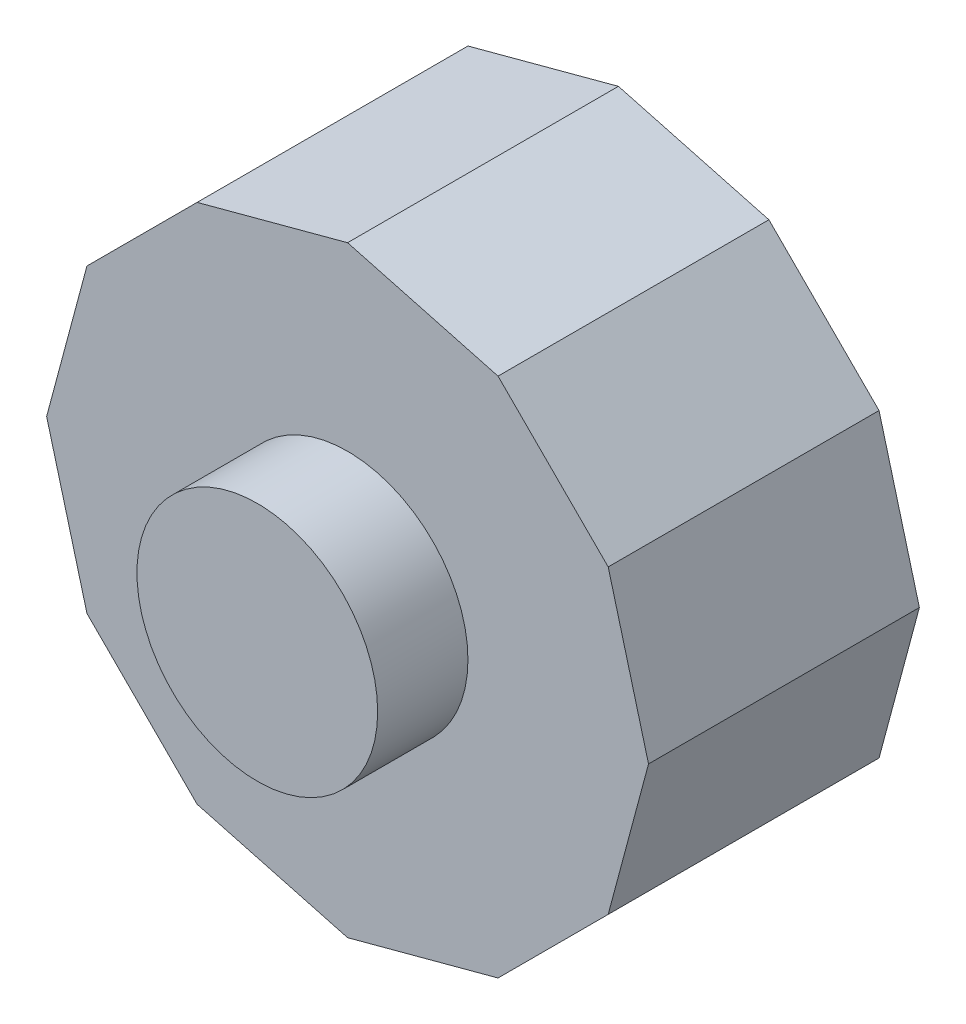
SolidWorks part; units mm, degrees
ref_plane "前视基准面" through (0, 0, 0) normal (0, 0, 1) x (1, 0, 0)
ref_plane "上视基准面" through (0, 0, 0) normal (0, 1, 0) x (1, 0, 0)
ref_plane "右视基准面" through (0, 0, 0) normal (1, 0, 0) x (0, 0, -1)
other "Configuration Table"
sketch "草图1" plane through (0, 0, 0) normal (0, 0, 1) x (1, 0, 0)
  circle A0 centre (0, 0) radius 8
extrude "凸台-拉伸1" add sketch "草图1" along normal blind 24
sketch "草图2" plane through (0, 0, 0) normal (0, 0, 1) x (1, 0, 0)
  circle A0 centre (0, 0) radius 42
extrude "凸台-拉伸2" add sketch "草图2" along normal blind 18
sketch "草图3" plane through (0, 0, 18) normal (0, 0, 1) x (1, 0, 0)
  line L0 (20, 0) -> (17.3205, 10)
  line L1 (17.3205, 10) -> (10, 17.3205)
  line L2 (10, 17.3205) -> (0, 20)
  line L3 (0, 20) -> (-10, 17.3205)
  line L4 (-10, 17.3205) -> (-17.3205, 10)
  line L5 (-17.3205, 10) -> (-20, 0)
  line L6 (-20, 0) -> (-17.3205, -10)
  line L7 (-17.3205, -10) -> (-10, -17.3205)
  line L8 (-10, -17.3205) -> (0, -20)
  line L9 (0, -20) -> (10, -17.3205)
  line L10 (10, -17.3205) -> (17.3205, -10)
  line L11 (17.3205, -10) -> (20, 0)
extrude "切除-拉伸1" cut sketch "草图3" against normal through all flip side to cut
